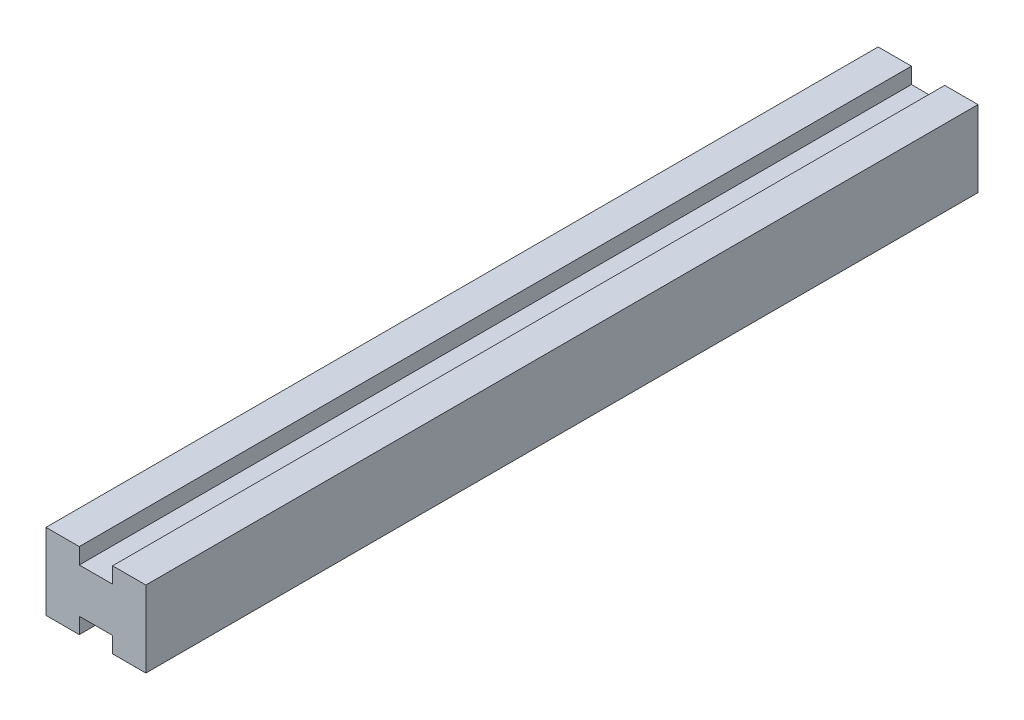
SolidWorks part; units mm, degrees
ref_plane "Front Plane" through (0, 0, 0) normal (0, 0, 1) x (1, 0, 0)
ref_plane "Top Plane" through (0, 0, 0) normal (0, 1, 0) x (1, 0, 0)
ref_plane "Right Plane" through (0, 0, 0) normal (1, 0, 0) x (0, 0, -1)
sketch "Sketch1" plane through (0, 0, 0) normal (0, 0, 1) x (1, 0, 0)
  line L0 (-2.4, 0) -> (0, 0) construction
  line L2 (3.6, -1.6) -> (3.6, 1.6)
  line L4 (-3.6, -1.6) -> (-3.6, 1.6)
  line L5 (3.6, -1.6) -> (-3.6, 1.6) construction
  line L6 (3.6, 1.6) -> (-3.6, -1.6) construction
  line L7 (0, 0) -> (2.4, 0) construction
  line L8 (-1.2, 2.75) -> (-3.6, 2.75)
  line L9 (-1.2, 2.75) -> (-1.2, 1.6)
  line L10 (-1.2, -2.75) -> (-3.6, -2.75)
  line L11 (-3.6, 2.75) -> (-3.6, -2.75)
  line L12 (-1.2, 2.75) -> (-3.6, -2.75) construction
  line L13 (-1.2, -2.75) -> (-3.6, 2.75) construction
  line L14 (-1.2, -1.6) -> (-1.2, -2.75)
  line L15 (1.2, 2.75) -> (3.6, 2.75)
  line L16 (1.2, 2.75) -> (1.2, 1.6)
  line L17 (1.2, -2.75) -> (3.6, -2.75)
  line L18 (3.6, 2.75) -> (3.6, -2.75)
  line L19 (1.2, 2.75) -> (3.6, -2.75) construction
  line L20 (1.2, -2.75) -> (3.6, 2.75) construction
  line L21 (1.2, -1.6) -> (1.2, -2.75)
  line L22 (1.2, -1.6) -> (-1.2, -1.6)
  line L23 (1.2, 1.6) -> (-1.2, 1.6)
  point P0 (0, 0)
  dimension "D1" = 7.2
  dimension "D2" = 3.2
  dimension "D3" = 2.4
  dimension "D4" = 5.5
  dimension "D5" = 2.4
  dimension "D6" = 2.4
  dimension "D7" = 5.5
  dimension "D8" = 2.4
extrude "Boss-Extrude1" add sketch "Sketch1" along normal blind 60 contours L8 L11 L10 L14 L22 L21 L17 L18 L15 L16 L23 L9
